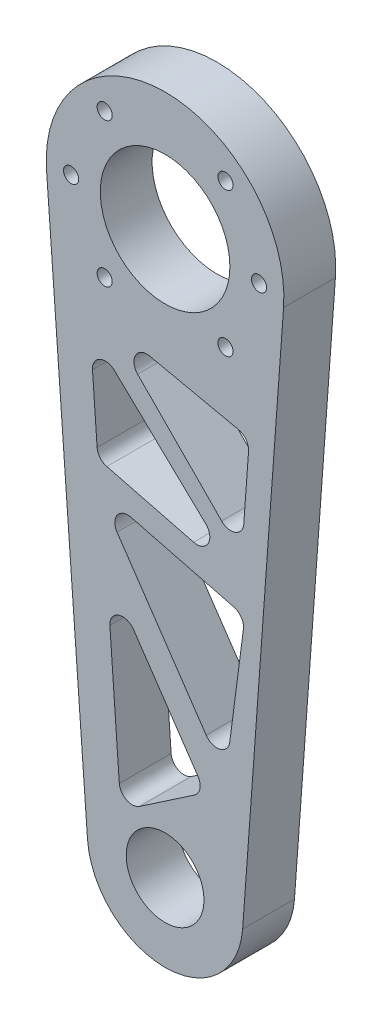
SolidWorks part; units mm, degrees
material "Thornel Mat VMA"
ref_plane "前视基准面" through (0, 0, 0) normal (0, 0, 1) x (1, 0, 0)
ref_plane "上视基准面" through (0, 0, 0) normal (0, 1, 0) x (1, 0, 0)
ref_plane "右视基准面" through (0, 0, 0) normal (1, 0, 0) x (0, 0, -1)
sketch "草图1" plane through (0, 0, 0) normal (0, 0, 1) x (1, 0, 0)
  line L0 (-17.9519, -131.3154) -> (-27.4265, -2.0096)
  line L1 (17.9519, -131.3154) -> (27.4265, -2.0096)
  line L2 (0, 80.1962) -> (0, -162.4079) construction
  arc A0 (27.4265, -2.0096) -> (-27.4265, -2.0096) centre (0, 0) ccw
  arc A1 (-17.9519, -131.3154) -> (17.9519, -131.3154) centre (0, -130) ccw
  dimension "D1" = 55
  dimension "D2" = 36
  dimension "D3" = 130
extrude "凸台-拉伸1" add sketch "草图1" along normal blind 12
sketch "草图2" plane through (0, 0, 12) normal (0, 0, 1) x (1, 0, 0)
  line L0 (-21.75, 0) -> (21.75, 0) construction
  line L1 (-13.9806, 16.6615) -> (13.9806, -16.6615) construction
  point P4 (0, 0)
  circle B0 centre (-13.9806, 16.6615) radius 1.75
  circle B1 centre (-21.75, 0) radius 1.75
  circle B2 centre (-13.9806, -16.6615) radius 1.75
  circle B3 centre (13.9806, -16.6615) radius 1.75
  circle B4 centre (21.75, 0) radius 1.75
  circle B5 centre (13.9806, 16.6615) radius 1.75
sketch_block_instance "wai-1"
sketch_block "wai"
extrude "切除-拉伸1" cut sketch "草图2" against normal blind 15
sketch "草图3" plane through (0, 0, 12) normal (0, 0, 1) x (1, 0, 0)
  circle A0 centre (0, 0) radius 15
  dimension "D1" = 30
extrude "切除-拉伸2" cut sketch "草图3" against normal through all
sketch "草图4" plane through (0, 0, 12) normal (0, 0, 1) x (1, 0, 0)
  circle A0 centre (0, -130) radius 9
  arc A1 (-17.9519, -131.3154) -> (17.9519, -131.3154) centre (0, -130) ccw construction
  dimension "D1" = 18
extrude "切除-拉伸3" cut sketch "草图4" against normal through all
sketch "草图5" plane through (0, 0, 12) normal (0, 0, 1) x (1, 0, 0)
  line L0 (-13.4355, -25.0821) -> (19.5161, -32.2373)
  line L1 (19.5161, -32.2373) -> (17.7274, -56.649)
  line L2 (17.7274, -56.649) -> (-13.4355, -25.0821)
  line L3 (-17.3581, -28.8283) -> (-15.5785, -53.7833)
  line L4 (-15.5785, -53.7833) -> (17.7274, -62.2997)
  line L5 (17.7274, -62.2997) -> (-17.3581, -28.8283)
  line L6 (-15.566, -59.7424) -> (18.4806, -68.4481)
  line L7 (18.4806, -68.4481) -> (13.9454, -103.2117)
  line L8 (13.9454, -103.2117) -> (-15.566, -59.7424)
  line L9 (-13.5729, -74.6748) -> (9.2896, -108.3505)
  line L10 (9.2896, -108.3505) -> (-10.2266, -121.6001)
  line L11 (-10.2266, -121.6001) -> (-13.5729, -74.6748)
  line L12 (17.9519, -131.3154) -> (27.4265, -2.0096) construction
extrude "切除-拉伸4" cut sketch "草图5" against normal blind 46
fillet "圆角1" radius 3 12 edges at (19.5161, -32.2373, 6) (17.7274, -56.649, 6) (-13.5729, -74.6748, 6) (9.2896, -108.3505, 6) (-10.2266, -121.6001, 6) (18.4806, -68.4481, 6) (13.9454, -103.2117, 6) (-15.566, -59.7424, 6) (-15.5785, -53.7833, 6) (-17.3581, -28.8283, 6) (17.7274, -62.2997, 6) (-13.4355, -25.0821, 6)
